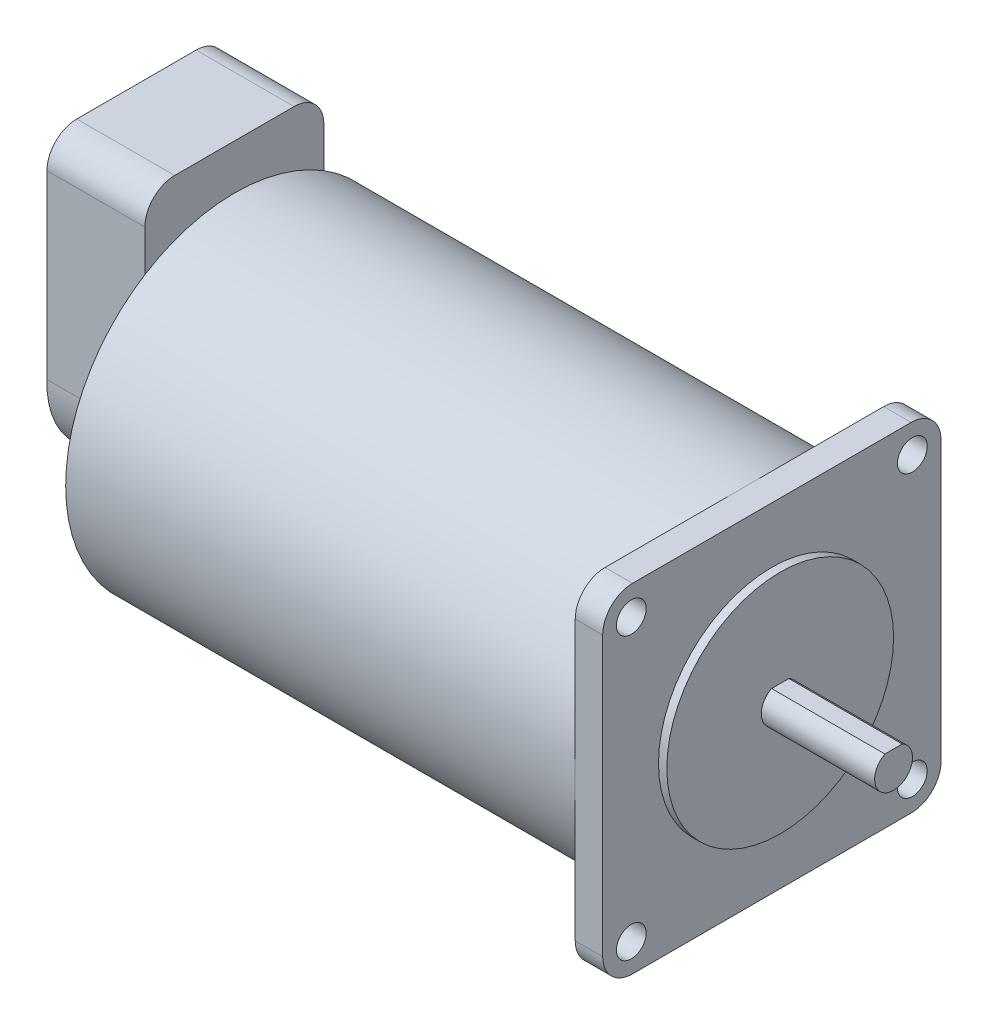
SolidWorks part; units mm, degrees
ref_plane "Front Plane" through (0, 0, 0) normal (0, 0, 1) x (1, 0, 0)
ref_plane "Top Plane" through (0, 0, 0) normal (0, 1, 0) x (1, 0, 0)
ref_plane "Right Plane" through (0, 0, 0) normal (1, 0, 0) x (0, 0, -1)
sketch "Sketch1" plane through (0, 0, 0) normal (1, 0, 0) x (0, 0, -1)
  circle A0 centre (0, 0) radius 28.35
  dimension "D1" = 56.7
extrude "Boss-Extrude1" add sketch "Sketch1" along normal blind 85.4
sketch "Sketch2" plane through (85.4, 0, 0) normal (1, 0, 0) x (0, 0, -1)
  line L0 (-28.35, 28.35) -> (-23.55, 23.55) construction
  line L1 (-28.35, 28.35) -> (28.35, 28.35)
  line L2 (-28.35, 28.35) -> (-28.35, -28.35)
  line L3 (-28.35, -28.35) -> (28.35, -28.35)
  line L4 (28.35, 28.35) -> (28.35, -28.35)
  line L5 (-23.55, 23.55) -> (23.55, 23.55) construction
  line L6 (-23.55, 23.55) -> (-23.55, -23.55) construction
  line L7 (-23.55, -23.55) -> (23.55, -23.55) construction
  line L8 (23.55, 23.55) -> (23.55, -23.55) construction
  line L9 (-23.55, 23.55) -> (0, 0) construction
  line L10 (0, 0) -> (23.55, -23.55) construction
  line L11 (23.55, -23.55) -> (28.35, -28.35) construction
  line L12 (-28.35, -28.35) -> (-23.55, -23.55) construction
  line L13 (-23.55, -23.55) -> (0, 0) construction
  line L14 (0, 0) -> (23.55, 23.55) construction
  line L15 (23.55, 23.55) -> (28.35, 28.35) construction
  circle A0 centre (-23.55, 23.55) radius 2.5
  circle A1 centre (23.55, 23.55) radius 2.5
  circle A2 centre (23.55, -23.55) radius 2.5
  circle A3 centre (-23.55, -23.55) radius 2.5
  dimension "D3" = 5
  dimension "D1" = 47.1
  dimension "D2" = 56.7
extrude "Boss-Extrude2" add sketch "Sketch2" along normal blind 4.6
sketch "Sketch3" plane through (90, 0, 0) normal (1, 0, 0) x (0, 0, -1)
  circle A0 centre (0, 0) radius 19
  arc A1 (-28.35, 0) -> (0, -28.35) centre (0, 0) ccw construction
  dimension "D1" = 38
extrude "Boss-Extrude3" add sketch "Sketch3" along normal blind 1.4
sketch "Sketch4" plane through (91.4, 0, 0) normal (1, 0, 0) x (0, 0, -1)
  line L0 (-1.4491, 2.825) -> (1.4491, 2.825)
  arc A0 (1.4491, 2.825) -> (-1.4491, 2.825) centre (0, 0) cw
  arc A1 (-1.4491, 2.825) -> (1.4491, 2.825) centre (0, 0) cw construction
  circle A2 centre (0, 0) radius 19 construction
  circle A3 centre (0, 0) radius 19 construction
  dimension "D1" = 3.175
  dimension "D2" = 6
extrude "Boss-Extrude4" add sketch "Sketch4" along normal blind 19
fillet "Fillet1" radius 5 4 edges at (87.7, -28.35, -28.35) (87.7, 28.35, -28.35) (87.7, -28.35, 28.35) (87.7, 28.35, 28.35)
sketch "Sketch5" plane through (0, 0, 0) normal (-1, 0, 0) x (0, 0, 1)
  line L0 (-14.9198, -2.2684) -> (-14.9198, 30.9087)
  line L1 (-9.9198, 35.9087) -> (10.0802, 35.9087)
  line L2 (15.0802, 0.5796) -> (15.0802, 30.9087)
  arc A0 (-14.9198, -2.2684) -> (15.0802, 0.5796) centre (0, 0) ccw
  arc A1 (10.0802, 35.9087) -> (15.0802, 30.9087) centre (10.0802, 30.9087) cw
  arc A2 (-14.9198, 30.9087) -> (-9.9198, 35.9087) centre (-9.9198, 30.9087) cw
  circle A3 centre (0, 0) radius 28.35 construction
  dimension "D1" = 30
  dimension "D3" = 5
  dimension "D2" = 51
extrude "Boss-Extrude5" add sketch "Sketch5" along normal blind 16.4
